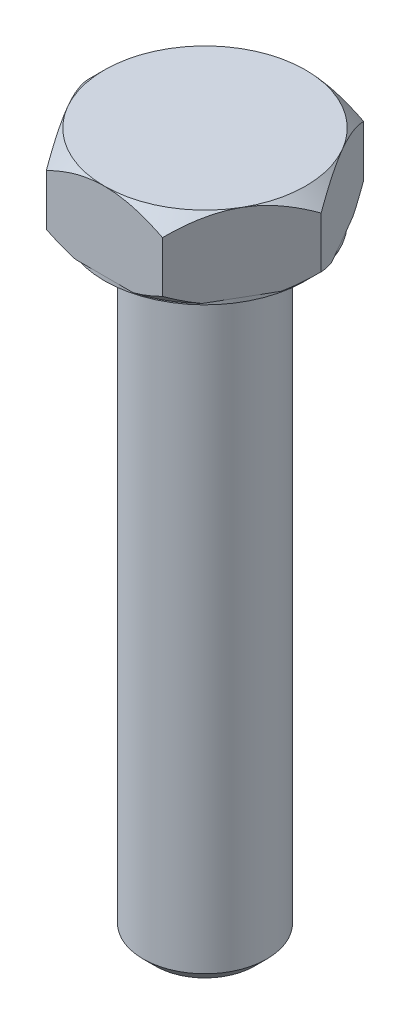
SolidWorks part; units mm, degrees
material "Cast Stainless Steel"
ref_plane "Front Plane" through (0, 0, 0) normal (0, 0, 1) x (1, 0, 0)
ref_plane "Top Plane" through (0, 0, 0) normal (0, 1, 0) x (1, 0, 0)
ref_plane "Right Plane" through (0, 0, 0) normal (1, 0, 0) x (0, 0, -1)
sketch "Sketch1" plane through (0, 0, 0) normal (0, 1, 0) x (1, 0, 0)
  line L0 (0, 0) -> (7.5056, 0) construction
  line L1 (7.5056, 0) -> (3.7528, 6.5)
  line L2 (3.7528, 6.5) -> (-3.7528, 6.5)
  line L3 (-3.7528, 6.5) -> (-7.5056, 0)
  line L4 (-7.5056, 0) -> (-3.7528, -6.5)
  line L5 (-3.7528, -6.5) -> (3.7528, -6.5)
  line L6 (3.7528, -6.5) -> (7.5056, 0)
  circle A0 centre (0, 0) radius 6.5 construction
  dimension "D1" = 13
extrude "Boss-Extrude1" add sketch "Sketch1" against normal blind 5.3
sketch "Sketch4" plane through (0, 0, 0) normal (1, 0, 0) x (0, 0, -1)
  line L0 (-6.5, 0) -> (-8.15, 0)
  line L1 (-8.15, 0) -> (-8.15, -1.65)
  line L2 (-8.15, -1.65) -> (-6.5, 0)
  line L3 (-6.5, -2.65) -> (6.5, -2.65) construction
  line L4 (-8.15, -3.65) -> (-6.5, -5.3)
  line L5 (-8.15, -5.3) -> (-8.15, -3.65)
  line L6 (-6.5, -5.3) -> (-8.15, -5.3)
  line L7 (0, 0) -> (0, -2.65) construction
  dimension "D1" = 45
  dimension "D2" = 2.65
  dimension "D3" = 1.65
  dimension "D4" = 13
revolve "Cut-Revolve1" cut sketch "Sketch4" angle 360 about L7
sketch "Sketch2" plane through (0, -5.3, 0) normal (0, -1, 0) x (1, 0, 0)
  circle A0 centre (0, 0) radius 6.5
  dimension "D1" = 13
extrude "Cut-Extrude1" cut sketch "Sketch2" against normal blind 0.265 flip side to cut
sketch "Sketch3" plane through (0, -5.3, 0) normal (0, -1, 0) x (1, 0, 0)
  circle A0 centre (0, 0) radius 4
  dimension "D1" = 8
extrude "Boss-Extrude2" add sketch "Sketch3" along normal blind 40
chamfer "Chamfer1" distance 0.8 angle 45 1 edges at (0, -45.3, -4)
equation "\"k\"= 5.3"
equation "\"e\"= 14.38"
equation "\"S\"= 13"
equation "\"L\"= 40"
equation "\"D1@Sketch1\"=\"S\""
equation "\"D1@Boss-Extrude1\"=\"k\""
equation "\"D1@Sketch2\"=\"S\""
equation "\"D1@Cut-Extrude1\"=\"k\"/20"
equation "\"d\"= 8"
equation "\"D1@Sketch3\"=\"d\""
equation "\"D1@Boss-Extrude2\"=\"L\""
equation "\"D2@Sketch4\"=\"k\"/2"
equation "\"D3@Sketch4\"=\"D2@Sketch4\"-1"
equation "\"D4@Sketch4\"=\"S\""
equation "\"D1@Chamfer1\"=\"d\"/10"
